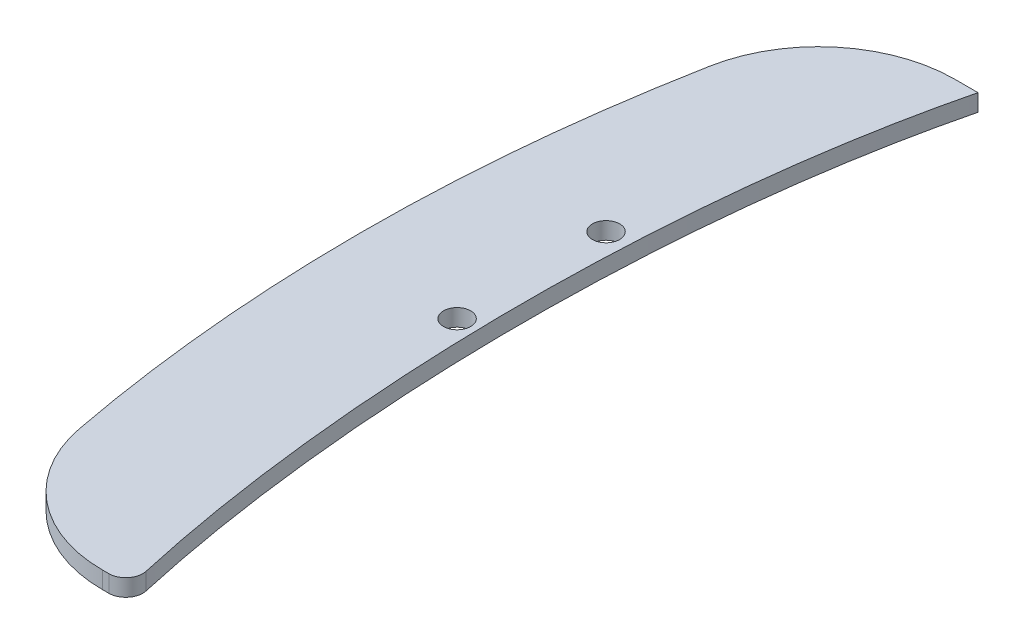
SolidWorks part; units mm, degrees
ref_plane "Plano frontal" through (0, 0, 0) normal (0, 0, 1) x (1, 0, 0)
ref_plane "Plano superior" through (0, 0, 0) normal (0, 1, 0) x (1, 0, 0)
ref_plane "Plano direito" through (0, 0, 0) normal (1, 0, 0) x (0, 0, -1)
sketch "Esboço1" plane through (0, 0, 0) normal (0, 1, 0) x (1, 0, 0)
  line L1 (11.0406, -63.0222) -> (11.9751, -63.0222)
  line L2 (11.222, 61.9778) -> (14.6282, 61.9778)
  line L4 (-14.8747, -63.0222) -> (14.6282, 61.9778) construction
  line L5 (-14.8747, 61.9778) -> (15.1253, -63.0222) construction
  circle A0 centre (5.0015, 16.9778) radius 2
  circle A1 centre (5.1253, -5.0219) radius 2
  arc A2 (-8.5956, -46.8192) -> (11.0406, -63.0222) centre (11.0406, -43.0222) ccw
  arc A3 (-8.436, 45.6605) -> (11.222, 61.9778) centre (11.222, 41.9778) cw
  arc A4 (11.9751, -63.0222) -> (14.4139, -59.9726) centre (11.9751, -60.5222) ccw
  spline S0 degree 3 poles (14.6282, 61.9778) (9.9619, 43.145) (5.8009, 0.1589) (10.36, -41.9836) (14.4139, -59.9726) knots 0 0 0 0 0.486127 0.972254 0.972254 0.972254 0.972254
  spline S1 degree 3 poles (-8.436, 45.6605) (-10.9284, 32.3565) (-14.3345, 2.3829) (-11.9605, -29.4177) (-8.5956, -46.8192) knots 0.12681 0.12681 0.12681 0.12681 0.438278 0.86648 0.86648 0.86648 0.86648
  point P1 (0, 0)
  point P14 (-14.8747, 51.9778)
  dimension "D4" = 4
  dimension "D7" = 20
  dimension "D2" = 2.5
  dimension "D1" = 125
  dimension "D5" = 45
  dimension "D6" = 22
extrude "Ressalto-extrusão1" add sketch "Esboço1" along normal blind 2.5
